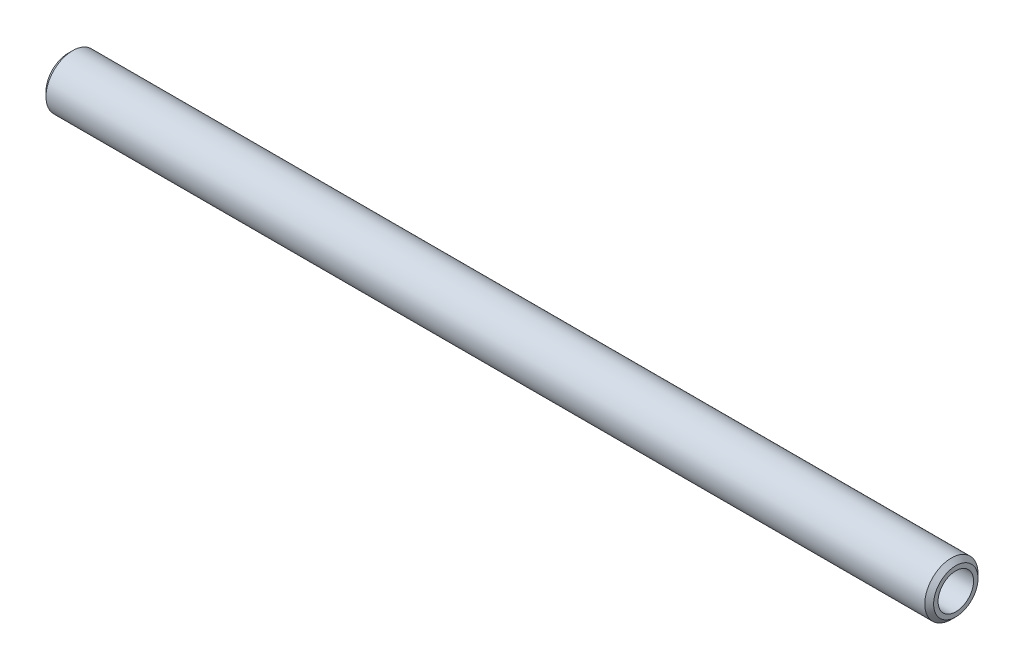
SolidWorks part; units mm, degrees
material "AISI 304"
ref_plane "Plan de face" through (0, 0, 0) normal (0, 0, 1) x (1, 0, 0)
ref_plane "Plan de dessus" through (0, 0, 0) normal (0, 1, 0) x (1, 0, 0)
ref_plane "Plan de droite" through (0, 0, 0) normal (1, 0, 0) x (0, 0, -1)
sketch "Esquisse1" plane through (0, 0, 0) normal (1, 0, 0) x (0, 0, -1)
  circle A0 centre (0, 0) radius 2
  circle A1 centre (0, 0) radius 3
  dimension "D1" = 6
  dimension "D2" = 4
extrude "Boss.-Extru.1" add sketch "Esquisse1" along normal mid plane 100
chamfer "Chanfrein1" distance 0.5 angle 45 2 edges at (-50, 0, -3) (50, 0, -3)
